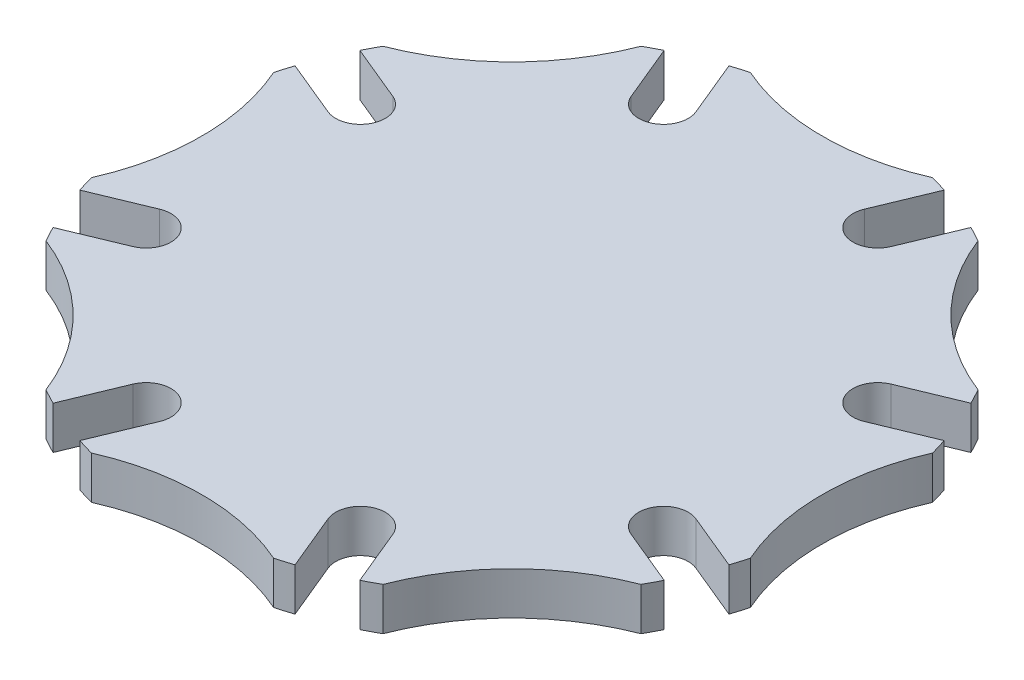
SolidWorks part; units mm, degrees
ref_plane "Front Plane" through (0, 0, 0) normal (0, 0, 1) x (1, 0, 0)
ref_plane "Top Plane" through (0, 0, 0) normal (0, 1, 0) x (1, 0, 0)
ref_plane "Right Plane" through (0, 0, 0) normal (1, 0, 0) x (0, 0, -1)
sketch "Sketch2" plane through (0, 0, 0) normal (0, 1, 0) x (1, 0, 0)
  line L0 (0, 0) -> (62.7561, 0) construction
  line L1 (62.7561, 0) -> (36.9552, 15.3073) construction
  line L2 (36.9552, 15.3073) -> (0, 0) construction
  line L3 (36.9552, 15.3073) -> (30.2627, 12.5352) construction
  line L4 (38.065, 12.6281) -> (31.3724, 9.856)
  line L5 (35.8454, 17.9866) -> (29.1529, 15.2145)
  line L6 (36.9552, -15.3073) -> (30.2627, -12.5352) construction
  line L7 (35.8454, -17.9866) -> (29.1529, -15.2145)
  line L8 (38.065, -12.6281) -> (31.3724, -9.856)
  line L9 (15.3073, -36.9552) -> (12.5352, -30.2627) construction
  line L10 (12.6281, -38.065) -> (9.856, -31.3724)
  line L11 (17.9866, -35.8454) -> (15.2145, -29.1529)
  line L12 (-15.3073, -36.9552) -> (-12.5352, -30.2627) construction
  line L13 (-17.9866, -35.8454) -> (-15.2145, -29.1529)
  line L14 (-12.6281, -38.065) -> (-9.856, -31.3724)
  line L15 (-36.9552, -15.3073) -> (-30.2627, -12.5352) construction
  line L16 (-38.065, -12.6281) -> (-31.3724, -9.856)
  line L17 (-35.8454, -17.9866) -> (-29.1529, -15.2145)
  line L18 (-36.9552, 15.3073) -> (-30.2627, 12.5352) construction
  line L19 (-35.8454, 17.9866) -> (-29.1529, 15.2145)
  line L20 (-38.065, 12.6281) -> (-31.3724, 9.856)
  line L21 (-15.3073, 36.9552) -> (-12.5352, 30.2627) construction
  line L22 (-12.6281, 38.065) -> (-9.856, 31.3724)
  line L23 (-17.9866, 35.8454) -> (-15.2145, 29.1529)
  line L24 (15.3073, 36.9552) -> (12.5352, 30.2627) construction
  line L25 (17.9866, 35.8454) -> (15.2145, 29.1529)
  line L26 (12.6281, 38.065) -> (9.856, 31.3724)
  circle A0 centre (36.9552, 15.3073) radius 2.5
  arc A1 (38.065, 12.6281) -> (35.8454, 17.9866) centre (36.9552, 15.3073) ccw
  arc A2 (29.1529, 15.2145) -> (31.3724, 9.856) centre (30.2627, 12.5352) ccw
  circle A3 centre (62.7561, 0) radius 30
  circle A4 centre (0, 0) radius 40
  circle A5 centre (0, 0) radius 32.7561
  circle A6 centre (62.7561, 0) radius 26.4496
  arc A7 (41.3963, 14.9112) -> (41.3963, -14.9112) centre (62.7561, 0) cw
  arc A8 (41.3963, 14.9112) -> (41.3963, -14.9112) centre (0, 0) cw
  circle A9 centre (44.3752, -44.3752) radius 26.4496
  arc A10 (35.8454, -17.9866) -> (38.065, -12.6281) centre (36.9552, -15.3073) ccw
  arc A11 (31.3724, -9.856) -> (29.1529, -15.2145) centre (30.2627, -12.5352) ccw
  circle A12 centre (0, -62.7561) radius 26.4496
  arc A13 (12.6281, -38.065) -> (17.9866, -35.8454) centre (15.3073, -36.9552) ccw
  arc A14 (15.2145, -29.1529) -> (9.856, -31.3724) centre (12.5352, -30.2627) ccw
  circle A15 centre (-44.3752, -44.3752) radius 26.4496
  arc A16 (-17.9866, -35.8454) -> (-12.6281, -38.065) centre (-15.3073, -36.9552) ccw
  arc A17 (-9.856, -31.3724) -> (-15.2145, -29.1529) centre (-12.5352, -30.2627) ccw
  circle A18 centre (-62.7561, 0) radius 26.4496
  arc A19 (-38.065, -12.6281) -> (-35.8454, -17.9866) centre (-36.9552, -15.3073) ccw
  arc A20 (-29.1529, -15.2145) -> (-31.3724, -9.856) centre (-30.2627, -12.5352) ccw
  circle A21 centre (-44.3752, 44.3752) radius 26.4496
  arc A22 (-35.8454, 17.9866) -> (-38.065, 12.6281) centre (-36.9552, 15.3073) ccw
  arc A23 (-31.3724, 9.856) -> (-29.1529, 15.2145) centre (-30.2627, 12.5352) ccw
  circle A24 centre (0, 62.7561) radius 26.4496
  arc A25 (-12.6281, 38.065) -> (-17.9866, 35.8454) centre (-15.3073, 36.9552) ccw
  arc A26 (-15.2145, 29.1529) -> (-9.856, 31.3724) centre (-12.5352, 30.2627) ccw
  circle A27 centre (44.3752, 44.3752) radius 26.4496
  arc A28 (17.9866, 35.8454) -> (12.6281, 38.065) centre (15.3073, 36.9552) ccw
  arc A29 (9.856, 31.3724) -> (15.2145, 29.1529) centre (12.5352, 30.2627) ccw
  point P3 (33.6089, 13.9213)
  point P15 (38.552, 10.665)
  point P22 (33.6089, -13.9213)
  point P31 (13.9213, -33.6089)
  point P40 (-13.9213, -33.6089)
  point P49 (-33.6089, -13.9213)
  point P58 (-33.6089, 13.9213)
  point P67 (-13.9213, 33.6089)
  point P76 (13.9213, 33.6089)
  point P84 (0, 0)
  dimension "D4" = 5
  dimension "D5" = 2.9
  dimension "D1" = 22.5
  dimension "D2" = 40
  dimension "D3" = 30
  dimension "D6" = 2
  dimension "D7" = 0.4
  dimension "D8" = 4
  dimension "D9" = 8
extrude "Boss-Extrude1" add sketch "Sketch2" along normal blind 5 contours A29 A5 A26 A23 A20 A17 A14 A11 A2 | A29 L26 A4 A24 L22 A26 A5 | A26 L23 A4 A21 L19 A23 A5 | A23 L20 A4 A18 L16 A20 A5 | A20 L17 A4 A15 L13 A17 A5 | A17 L14 A4 A12 L10 A14 A5 | A14 L11 A4 A9 L7 A11 A5 | A11 L8 A3 A5 | A6 A4 L4 A3 L8 | A5 A3 L4 A2 | A29 A5 A2 L5 A4 A27 L25
equation "\"angle\"= 22.5"
equation "\"driveR\"= 40"
equation "\"D1@Sketch2\"=\"angle\""
equation "\"D2@Sketch2\"=\"driveR\""
equation "\"wheelR\"= 30"
equation "\"D3@Sketch2\"=\"wheelR\""
equation "\"pin\"= 5"
equation "\"D4@Sketch2\"=\"pin\""
equation "\"D5@Sketch2\"=(\"pin\"/2)+\"tol\""
equation "\"tol\"= 0.4"
equation "\"D7@Sketch2\"=\"tol\""
